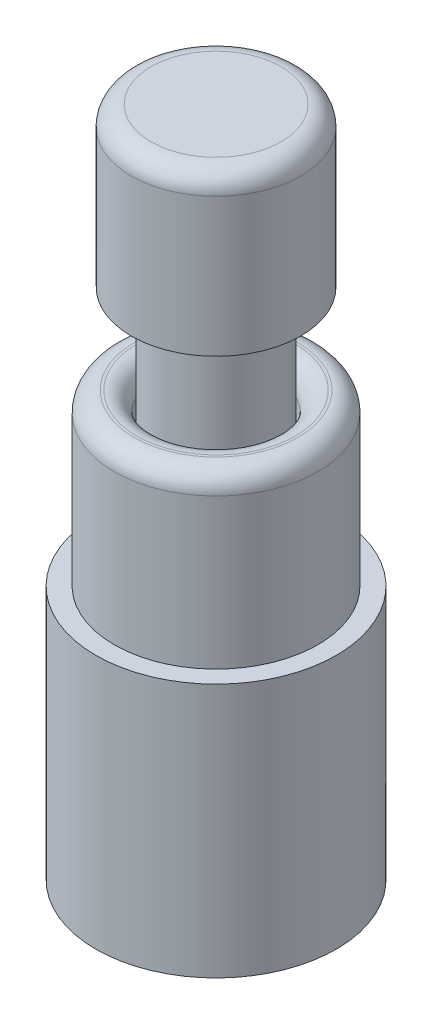
SolidWorks part; units mm, degrees
material "ABS"
ref_plane "Front Plane" through (0, 0, 0) normal (0, 0, 1) x (1, 0, 0)
ref_plane "Top Plane" through (0, 0, 0) normal (0, 1, 0) x (1, 0, 0)
ref_plane "Right Plane" through (0, 0, 0) normal (1, 0, 0) x (0, 0, -1)
sketch "Sketch1" plane through (0, 0, 0) normal (0, 1, 0) x (1, 0, 0)
  circle A0 centre (0, 0) radius 3.6
extrude "Boss-Extrude2" add sketch "Sketch1" along normal blind 6
sketch "Sketch4" plane through (0, 0, 0) normal (0, 1, 0) x (1, 0, 0)
  circle A0 centre (0, 0) radius 4.25
extrude "Boss-Extrude3" add sketch "Sketch4" against normal blind 9
sketch "Sketch5" plane through (0, 0, 0) normal (0, 1, 0) x (1, 0, 0)
  circle A0 centre (0, 0) radius 2
sketch "Sketch7" plane through (0, 6, 0) normal (0, 1, 0) x (1, 0, 0)
  circle A0 centre (0, 0) radius 2.1082
extrude "Cut-Extrude3" cut sketch "Sketch7" against normal blind 5.6
extrude "Boss-Extrude6" add sketch "Sketch5" along normal blind 9.156
fillet "Fillet3" radius 0.7 2 edges at (0, 6, 3.6) (0, 6, 2.1082)
sketch "Sketch9" plane through (0, 9.156, 0) normal (0, 1, 0) x (1, 0, 0)
  circle A0 centre (0, 0) radius 3
extrude "Boss-Extrude7" add sketch "Sketch9" along normal blind 5.6
fillet "Fillet4" radius 0.7 1 edges at (0, 14.756, 3)
